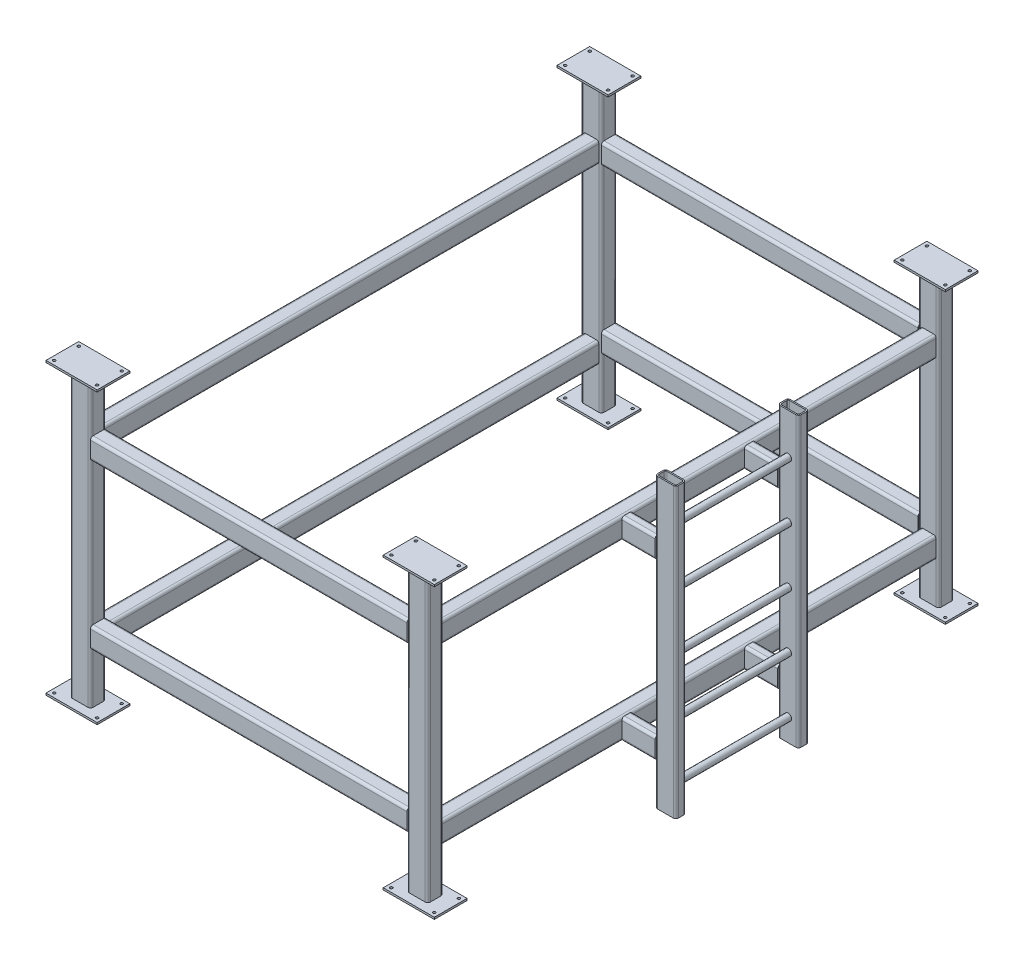
SolidWorks part; units mm, degrees
ref_plane "Front Plane" through (0, 0, 0) normal (0, 0, 1) x (1, 0, 0)
ref_plane "Top Plane" through (0, 0, 0) normal (0, 1, 0) x (1, 0, 0)
ref_plane "Right Plane" through (0, 0, 0) normal (1, 0, 0) x (0, 0, -1)
sketch "Sketch1" plane through (0, 0, 0) normal (0, 1, 0) x (1, 0, 0)
  line L0 (0, 1250) -> (0, -1250) construction
  line L1 (825, -1250) -> (-825, -1250) construction
  line L2 (825, -1250) -> (825, 1250) construction
  line L3 (825, 1250) -> (-825, 1250) construction
  line L4 (-825, -1250) -> (-825, 1250) construction
  line L5 (825, -1250) -> (-825, 1250) construction
  line L6 (825, 1250) -> (-825, -1250) construction
  point P0 (0, 0)
  dimension "D1" = 2500
  dimension "D2" = 1650
sketch3d "3DSketch1"
  line L0 (-825, 0, 1250) -> (-825, 1400, 1250)
  line L1 (825, 0, 1250) -> (825, 1400, 1250)
  line L2 (825, 0, -1250) -> (825, 1400, -1250)
  line L3 (-825, 0, -1250) -> (-825, 1400, -1250)
  line L4 (-825, 1100, 1250) -> (-825, 1100, -1250)
  line L5 (-825, 250, 1250) -> (-825, 250, -1250)
  line L6 (825, 1100, 1250) -> (825, 1100, -1250)
  line L7 (825, 250, 1250) -> (825, 250, -1250)
  line L8 (825, 0, 1250) -> (825, 0, -1250) construction
  line L9 (-825, 0, 1250) -> (-825, 0, -1250) construction
  dimension "D1" = 1400
  dimension "D2" = 300
  dimension "D3" = 850
  dimension "D4" = 300
  dimension "D5" = 850
other "Rectangular tube 4 X 3 X 0.25(1)"
ref_plane "Plane1" through (-825, 0, 1250) normal (0, 1, 0) x (0, 0, -1)
sketch "Sketch13" plane through (-825, 0, 1250) normal (0, 1, 0) x (0, 0, -1)
  line L0 (-25.4, -44.45) -> (25.4, -44.45)
  line L1 (-31.75, -38.1) -> (-31.75, 38.1)
  line L2 (25.4, 44.45) -> (-25.4, 44.45)
  line L3 (31.75, 38.1) -> (31.75, -38.1)
  line L4 (-25.4, -50.8) -> (25.4, -50.8)
  line L5 (-38.1, -38.1) -> (-38.1, 38.1)
  line L6 (25.4, 50.8) -> (-25.4, 50.8)
  line L7 (38.1, 38.1) -> (38.1, -38.1)
  line L8 (0, 0) -> (38.1, 0) construction
  line L9 (0, 0) -> (0, 50.8) construction
  arc A0 (38.1, 38.1) -> (25.4, 50.8) centre (25.4, 38.1) ccw
  arc A1 (25.4, -50.8) -> (38.1, -38.1) centre (25.4, -38.1) ccw
  arc A2 (-38.1, -38.1) -> (-25.4, -50.8) centre (-25.4, -38.1) ccw
  arc A3 (-25.4, 50.8) -> (-38.1, 38.1) centre (-25.4, 38.1) ccw
  arc A4 (-25.4, 44.45) -> (-31.75, 38.1) centre (-25.4, 38.1) ccw
  arc A5 (31.75, 38.1) -> (25.4, 44.45) centre (25.4, 38.1) ccw
  arc A6 (25.4, -44.45) -> (31.75, -38.1) centre (25.4, -38.1) ccw
  arc A7 (-31.75, -38.1) -> (-25.4, -44.45) centre (-25.4, -38.1) ccw
  point P3 (0, -50.8)
  point P4 (-38.1, 0)
  point P5 (0, 0)
  point P6 (38.1, -50.8)
  point P7 (-38.1, -50.8)
  point P8 (-38.1, 50.8)
  point P33 (0, 0)
  point P35 (38.1, 50.8)
  point P36 (38.1, 0)
  point P37 (0, 50.8)
  dimension "D1" = 12.7
  dimension "Thickness" = 6.35
  dimension "V_leg" = 101.6
  dimension "H_leg" = 76.2
other "Rectangular tube 4 X 3 X 0.25(2)"
ref_plane "Plane2" through (-825, 1100, 1250) normal (0, 0, -1) x (1, 0, 0)
sketch "Sketch14" plane through (-825, 1100, 1250) normal (0, 0, -1) x (1, 0, 0)
  line L0 (-25.4, -44.45) -> (25.4, -44.45)
  line L1 (-31.75, -38.1) -> (-31.75, 38.1)
  line L2 (25.4, 44.45) -> (-25.4, 44.45)
  line L3 (31.75, 38.1) -> (31.75, -38.1)
  line L4 (-25.4, -50.8) -> (25.4, -50.8)
  line L5 (-38.1, -38.1) -> (-38.1, 38.1)
  line L6 (25.4, 50.8) -> (-25.4, 50.8)
  line L7 (38.1, 38.1) -> (38.1, -38.1)
  line L8 (0, 0) -> (38.1, 0) construction
  line L9 (0, 0) -> (0, 50.8) construction
  arc A0 (38.1, 38.1) -> (25.4, 50.8) centre (25.4, 38.1) ccw
  arc A1 (25.4, -50.8) -> (38.1, -38.1) centre (25.4, -38.1) ccw
  arc A2 (-38.1, -38.1) -> (-25.4, -50.8) centre (-25.4, -38.1) ccw
  arc A3 (-25.4, 50.8) -> (-38.1, 38.1) centre (-25.4, 38.1) ccw
  arc A4 (-25.4, 44.45) -> (-31.75, 38.1) centre (-25.4, 38.1) ccw
  arc A5 (31.75, 38.1) -> (25.4, 44.45) centre (25.4, 38.1) ccw
  arc A6 (25.4, -44.45) -> (31.75, -38.1) centre (25.4, -38.1) ccw
  arc A7 (-31.75, -38.1) -> (-25.4, -44.45) centre (-25.4, -38.1) ccw
  point P3 (0, -50.8)
  point P4 (-38.1, 0)
  point P5 (0, 0)
  point P6 (38.1, -50.8)
  point P7 (-38.1, -50.8)
  point P8 (-38.1, 50.8)
  point P33 (0, 0)
  point P35 (38.1, 50.8)
  point P36 (38.1, 0)
  point P37 (0, 50.8)
  dimension "D1" = 12.7
  dimension "Thickness" = 6.35
  dimension "V_leg" = 101.6
  dimension "H_leg" = 76.2
other "Trim/Extend1"
sketch3d "3DSketch3"
  line L0 (774.2, 1400, -1250) -> (774.2, 1100, -1250) construction
  line L3 (774.2, 1400, -1275.4) -> (774.2, 1400, -1224.6) construction
  line L4 (774.2, 0, -1250) -> (774.2, 300, -1250) construction
  line L6 (774.2, 0, -1275.4) -> (774.2, 0, -1224.6) construction
  line L8 (774.2, 0, 1250) -> (774.2, 300, 1250) construction
  line L10 (774.2, 0, 1224.6) -> (774.2, 0, 1275.4) construction
  line L12 (774.2, 1400, 1250) -> (774.2, 1100, 1250) construction
  line L13 (774.2, 1400, 1224.6) -> (774.2, 1400, 1275.4) construction
  line L14 (-774.2, 0, 1250) -> (-774.2, 300, 1250) construction
  line L16 (-774.2, 0, 1275.4) -> (-774.2, 0, 1224.6) construction
  line L18 (-774.2, 1400, 1250) -> (-774.2, 1100, 1250) construction
  line L19 (-774.2, 1400, 1275.4) -> (-774.2, 1400, 1224.6) construction
  line L20 (-774.2, 1400, -1250) -> (-774.2, 1100, -1250) construction
  line L21 (-774.2, 1400, -1224.6) -> (-774.2, 1400, -1275.4) construction
  line L22 (-774.2, 0, -1250) -> (-774.2, 300, -1250) construction
  line L23 (-774.2, 0, -1224.6) -> (-774.2, 0, -1275.4) construction
  line L24 (-774.2, 300, 1250) -> (774.2, 300, 1250)
  line L25 (774.2, 1100, 1250) -> (-774.2, 1100, 1250)
  line L26 (-774.2, 1100, -1250) -> (774.2, 1100, -1250)
  line L27 (-774.2, 300, -1250) -> (774.2, 300, -1250)
  dimension "D1" = 300
other "Rectangular tube 4 X 3 X 0.25(3)"
ref_plane "Plane3" through (774.2, 1100, 1250) normal (-1, 0, 0) x (0, 0, 1)
sketch "Sketch15" plane through (774.2, 1100, 1250) normal (-1, 0, 0) x (0, 0, 1)
  line L0 (-25.4, -44.45) -> (25.4, -44.45)
  line L1 (-31.75, -38.1) -> (-31.75, 38.1)
  line L2 (25.4, 44.45) -> (-25.4, 44.45)
  line L3 (31.75, 38.1) -> (31.75, -38.1)
  line L4 (-25.4, -50.8) -> (25.4, -50.8)
  line L5 (-38.1, -38.1) -> (-38.1, 38.1)
  line L6 (25.4, 50.8) -> (-25.4, 50.8)
  line L7 (38.1, 38.1) -> (38.1, -38.1)
  line L8 (0, 0) -> (38.1, 0) construction
  line L9 (0, 0) -> (0, 50.8) construction
  arc A0 (38.1, 38.1) -> (25.4, 50.8) centre (25.4, 38.1) ccw
  arc A1 (25.4, -50.8) -> (38.1, -38.1) centre (25.4, -38.1) ccw
  arc A2 (-38.1, -38.1) -> (-25.4, -50.8) centre (-25.4, -38.1) ccw
  arc A3 (-25.4, 50.8) -> (-38.1, 38.1) centre (-25.4, 38.1) ccw
  arc A4 (-25.4, 44.45) -> (-31.75, 38.1) centre (-25.4, 38.1) ccw
  arc A5 (31.75, 38.1) -> (25.4, 44.45) centre (25.4, 38.1) ccw
  arc A6 (25.4, -44.45) -> (31.75, -38.1) centre (25.4, -38.1) ccw
  arc A7 (-31.75, -38.1) -> (-25.4, -44.45) centre (-25.4, -38.1) ccw
  point P3 (0, -50.8)
  point P4 (-38.1, 0)
  point P5 (0, 0)
  point P6 (38.1, -50.8)
  point P7 (-38.1, -50.8)
  point P8 (-38.1, 50.8)
  point P33 (0, 0)
  point P35 (38.1, 50.8)
  point P36 (38.1, 0)
  point P37 (0, 50.8)
  dimension "D1" = 12.7
  dimension "Thickness" = 6.35
  dimension "V_leg" = 101.6
  dimension "H_leg" = 76.2
sketch "Sketch16" plane through (0, 1400, 0) normal (0, 1, 0) x (1, 0, 0)
  line L0 (-872.0803, -1284.3803) -> (-777.9197, -1215.6197) construction
  line L1 (0, 0) -> (0, -1250) construction
  line L2 (-700, -1170) -> (-950, -1170)
  line L3 (-700, -1170) -> (-700, -1330)
  line L4 (-700, -1330) -> (-950, -1330)
  line L5 (-950, -1170) -> (-950, -1330)
  line L6 (-700, -1170) -> (-950, -1330) construction
  line L7 (-700, -1330) -> (-950, -1170) construction
  line L8 (-720, -1310) -> (-930, -1310)
  line L9 (-720, -1310) -> (-720, -1190)
  line L10 (-720, -1190) -> (-930, -1190)
  line L11 (-930, -1310) -> (-930, -1190)
  line L12 (-720, -1310) -> (-930, -1190) construction
  line L13 (-720, -1190) -> (-930, -1310) construction
  line L15 (0, 0) -> (-825, 0) construction
  line L17 (720, -1190) -> (930, -1310) construction
  line L18 (720, -1310) -> (930, -1190) construction
  line L19 (700, -1330) -> (950, -1170) construction
  line L20 (700, -1170) -> (950, -1330) construction
  line L21 (872.0803, -1284.3803) -> (777.9197, -1215.6197) construction
  line L22 (930, -1310) -> (930, -1190)
  line L23 (720, -1190) -> (930, -1190)
  line L24 (720, -1310) -> (720, -1190)
  line L25 (720, -1310) -> (930, -1310)
  line L26 (950, -1170) -> (950, -1330)
  line L27 (700, -1330) -> (950, -1330)
  line L28 (700, -1170) -> (700, -1330)
  line L29 (700, -1170) -> (950, -1170)
  line L30 (872.0803, 1284.3803) -> (777.9197, 1215.6197) construction
  line L31 (700, 1170) -> (950, 1330) construction
  line L32 (700, 1330) -> (950, 1170) construction
  line L33 (720, 1310) -> (930, 1190) construction
  line L34 (720, 1190) -> (930, 1310) construction
  line L35 (-720, 1190) -> (-930, 1310) construction
  line L36 (-720, 1310) -> (-930, 1190) construction
  line L37 (-700, 1330) -> (-950, 1170) construction
  line L38 (-700, 1170) -> (-950, 1330) construction
  line L39 (-872.0803, 1284.3803) -> (-777.9197, 1215.6197) construction
  line L40 (700, 1170) -> (950, 1170)
  line L41 (700, 1170) -> (700, 1330)
  line L42 (700, 1330) -> (950, 1330)
  line L43 (950, 1170) -> (950, 1330)
  line L44 (720, 1310) -> (930, 1310)
  line L45 (720, 1310) -> (720, 1190)
  line L46 (720, 1190) -> (930, 1190)
  line L47 (930, 1310) -> (930, 1190)
  line L48 (-930, 1310) -> (-930, 1190)
  line L49 (-720, 1190) -> (-930, 1190)
  line L50 (-720, 1310) -> (-720, 1190)
  line L51 (-720, 1310) -> (-930, 1310)
  line L52 (-950, 1170) -> (-950, 1330)
  line L53 (-700, 1330) -> (-950, 1330)
  line L54 (-700, 1170) -> (-700, 1330)
  line L55 (-700, 1170) -> (-950, 1170)
  line L58 (-774.2, -1250) -> (774.2, -1250) construction
  arc A0 (-875.8, -1275.4) -> (-863.1, -1288.1) centre (-863.1, -1275.4) ccw construction
  arc A1 (-774.2, -1224.6) -> (-786.9, -1211.9) centre (-786.9, -1224.6) ccw construction
  circle A2 centre (-930, -1190) radius 6.5
  circle A3 centre (-720, -1190) radius 6.5
  circle A4 centre (-720, -1310) radius 6.5
  circle A5 centre (-930, -1310) radius 6.5
  circle A6 centre (930, -1310) radius 6.5
  circle A7 centre (720, -1310) radius 6.5
  circle A8 centre (720, -1190) radius 6.5
  circle A9 centre (930, -1190) radius 6.5
  circle A10 centre (930, 1190) radius 6.5
  circle A11 centre (720, 1190) radius 6.5
  circle A12 centre (720, 1310) radius 6.5
  circle A13 centre (930, 1310) radius 6.5
  circle A14 centre (-930, 1310) radius 6.5
  circle A15 centre (-720, 1310) radius 6.5
  circle A16 centre (-720, 1190) radius 6.5
  circle A17 centre (-930, 1190) radius 6.5
  point P8 (-825, -1250)
  point P13 (-825, -1250)
  point P44 (825, -1250)
  point P73 (825, 1250)
  point P74 (-825, 1250)
  arc M15 (786.9, -1281.75) -> (780.55, -1275.4) centre (786.9, -1275.4) cw
  line M16 (780.55, -1275.4) -> (780.55, -1224.6)
  arc M17 (780.55, -1224.6) -> (786.9, -1218.25) centre (786.9, -1224.6) cw
  line M18 (786.9, -1218.25) -> (863.1, -1218.25)
  arc M19 (863.1, -1218.25) -> (869.45, -1224.6) centre (863.1, -1224.6) cw
  line M20 (869.45, -1224.6) -> (869.45, -1275.4)
  arc M21 (869.45, -1275.4) -> (863.1, -1281.75) centre (863.1, -1275.4) cw
  line M22 (863.1, -1281.75) -> (786.9, -1281.75)
  arc M23 (786.9, -1211.9) -> (774.2, -1224.6) centre (786.9, -1224.6) ccw
  line M24 (774.2, -1224.6) -> (774.2, -1275.4)
  arc M25 (774.2, -1275.4) -> (786.9, -1288.1) centre (786.9, -1275.4) ccw
  line M26 (786.9, -1288.1) -> (863.1, -1288.1)
  arc M27 (863.1, -1288.1) -> (875.8, -1275.4) centre (863.1, -1275.4) ccw
  line M28 (875.8, -1275.4) -> (875.8, -1224.6)
  arc M29 (875.8, -1224.6) -> (863.1, -1211.9) centre (863.1, -1224.6) ccw
  line M30 (863.1, -1211.9) -> (786.9, -1211.9)
  dimension "D3" = 13
  dimension "D1" = 250
  dimension "D2" = 160
  dimension "D4" = 210
  dimension "D5" = 120
extrude "Boss-Extrude1" add sketch "Sketch16" along normal blind 9.525 separate body contours L2 L5 L4 L3 A5 L11 A2 L10 A3 L9 A4 L8 | A5 L8 A4 L9 A3 L10 A2 L11 | M15 M22 M21 M20 M19 M18 M17 M16 | L22 A9 L23 A8 L24 A7 L25 A6 M23 M30 M29 M28 M27 M26 M25 M24 | L29 L28 L27 L26 L23 A9 L22 A6 L25 A7 L24 A8 | L40 L43 L42 L41 A13 L47 A10 L46 A11 L45 A12 L44 | A13 L44 A12 L45 A11 L46 A10 L47 | L55 L54 L53 L52 L49 A17 L48 A14 L51 A15 L50 A16 | L48 A17 L49 A16 L50 A15 L51 A14 | M30 M23 M24 M25 M26 M27 M28 M29 M22 M15 M16 M17 M18 M19 M20 M21
ref_plane "Plane4" through (0, 700, 0) normal (0, -1, 0) x (-1, 0, 0)
mirror "Mirror1" about plane through (0, 700, 0) normal (0, -1, 0) of "Boss-Extrude1"
sketch "Sketch17" plane through (863.1, 0, 0) normal (1, 0, 0) x (0, 0, -1)
  line L0 (0, 1100) -> (0, 250) construction
  line L1 (300, 250) -> (-300, 250) construction
  line L2 (300, 250) -> (300, 1100) construction
  line L3 (300, 1100) -> (-300, 1100) construction
  line L4 (-300, 250) -> (-300, 1100) construction
  line L5 (300, 250) -> (-300, 1100) construction
  line L6 (300, 1100) -> (-300, 250) construction
  line L7 (-1211.9, 250) -> (-300, 250) construction
  line L9 (-1211.9, 288.1) -> (-1211.9, 211.9) construction
  line L10 (-1211.9, 1100) -> (-300, 1100) construction
  line L11 (-1211.9, 1138.1) -> (-1211.9, 1061.9) construction
  point P0 (0, 675)
  dimension "D1" = 600
sketch3d "3DSketch4"
  line L0 (863.1, 1100, 300) -> (1076.4048, 1100, 300)
  line L1 (863.1, 250, 300) -> (1076.4048, 250, 300)
  line L2 (863.1, 1100, -300) -> (1076.4048, 1100, -300)
  line L3 (863.1, 250, -300) -> (1076.4048, 250, -300)
  line L4 (1076.4048, 1409.53, -300) -> (1076.4048, 0, -300)
  line L5 (1076.4048, 1409.53, 300) -> (1076.4048, 0, 300)
  dimension "D1" = 309.53
  dimension "D2" = 1409.53
  dimension "D3" = 309.53
other "Rectangular tube 4 X 2 X 0.25(1)"
ref_plane "Plane5" through (863.1, 1100, 300) normal (1, 0, 0) x (0, 0, -1)
sketch "Sketch113" plane through (863.1, 1100, 300) normal (1, 0, 0) x (0, 0, -1)
  line L0 (-12.7, -44.45) -> (12.7, -44.45)
  line L1 (-19.05, -38.1) -> (-19.05, 38.1)
  line L2 (12.7, 44.45) -> (-12.7, 44.45)
  line L3 (19.05, 38.1) -> (19.05, -38.1)
  line L4 (-12.7, -50.8) -> (12.7, -50.8)
  line L5 (-25.4, -38.1) -> (-25.4, 38.1)
  line L6 (12.7, 50.8) -> (-12.7, 50.8)
  line L7 (25.4, 38.1) -> (25.4, -38.1)
  line L8 (0, 0) -> (25.4, 0) construction
  line L9 (0, 0) -> (0, 50.8) construction
  arc A0 (25.4, 38.1) -> (12.7, 50.8) centre (12.7, 38.1) ccw
  arc A1 (12.7, -50.8) -> (25.4, -38.1) centre (12.7, -38.1) ccw
  arc A2 (-25.4, -38.1) -> (-12.7, -50.8) centre (-12.7, -38.1) ccw
  arc A3 (-12.7, 50.8) -> (-25.4, 38.1) centre (-12.7, 38.1) ccw
  arc A4 (-12.7, 44.45) -> (-19.05, 38.1) centre (-12.7, 38.1) ccw
  arc A5 (19.05, 38.1) -> (12.7, 44.45) centre (12.7, 38.1) ccw
  arc A6 (12.7, -44.45) -> (19.05, -38.1) centre (12.7, -38.1) ccw
  arc A7 (-19.05, -38.1) -> (-12.7, -44.45) centre (-12.7, -38.1) ccw
  point P3 (0, -50.8)
  point P4 (-25.4, 0)
  point P5 (0, 0)
  point P6 (25.4, -50.8)
  point P7 (-25.4, -50.8)
  point P8 (-25.4, 50.8)
  point P33 (0, 0)
  point P35 (25.4, 50.8)
  point P36 (25.4, 0)
  point P37 (0, 50.8)
  dimension "D1" = 12.7
  dimension "Thickness" = 6.35
  dimension "V_leg" = 101.6
  dimension "H_leg" = 50.8
sketch3d "3DSketch5"
  line L0 (1076.4048, 1409.53, 274.6) -> (1076.4048, 0, 274.6) construction
  line L1 (1038.3048, 1409.53, 274.6) -> (1114.5048, 1409.53, 274.6) construction
  line L2 (1038.3048, 0, 274.6) -> (1114.5048, 0, 274.6) construction
  line L3 (1076.4048, 1409.53, -274.6) -> (1076.4048, 0, -274.6) construction
  line L4 (1114.5048, 1409.53, -274.6) -> (1038.3048, 1409.53, -274.6) construction
  line L5 (1114.5048, 0, -274.6) -> (1038.3048, 0, -274.6) construction
  line L6 (1076.4048, 1209.53, 274.6) -> (1076.4048, 1209.53, -274.6)
  line L7 (1076.4048, 934.53, 274.6) -> (1076.4048, 934.53, -274.6)
  line L9 (1076.4048, 384.53, 274.6) -> (1076.4048, 384.53, -274.6)
  line L10 (1076.4048, 659.53, 274.6) -> (1076.4048, 659.53, -274.6)
  line L11 (1076.4048, 109.53, 274.6) -> (1076.4048, 109.53, -274.6)
  point P20 (1076.4048, 659.53, 0)
  dimension "D1" = 200
  dimension "D2" = 200
  dimension "D3" = 275
  dimension "D4" = 275
  dimension "D5" = 275
  dimension "D6" = 275
other "Pipe 1.0 SCH 40(1)"
ref_plane "Plane6" through (1076.4048, 1209.53, 274.6) normal (0, 0, -1) x (1, 0, 0)
sketch "Sketch114" plane through (1076.4048, 1209.53, 274.6) normal (0, 0, -1) x (1, 0, 0)
  circle A0 centre (0, 0) radius 13.3223
  circle A1 centre (0, 0) radius 16.7005
  circle A2 centre (0, 0) radius 12.7 construction
  point P5 (0, 16.7005)
  point P6 (0, -16.7005)
  point P7 (-16.7005, 0)
  point P8 (16.7005, 0)
  point P9 (0, 0)
  dimension "In_dia" = 26.6446
  dimension "Out_dia" = 33.401
  dimension "D1" = 25.4
